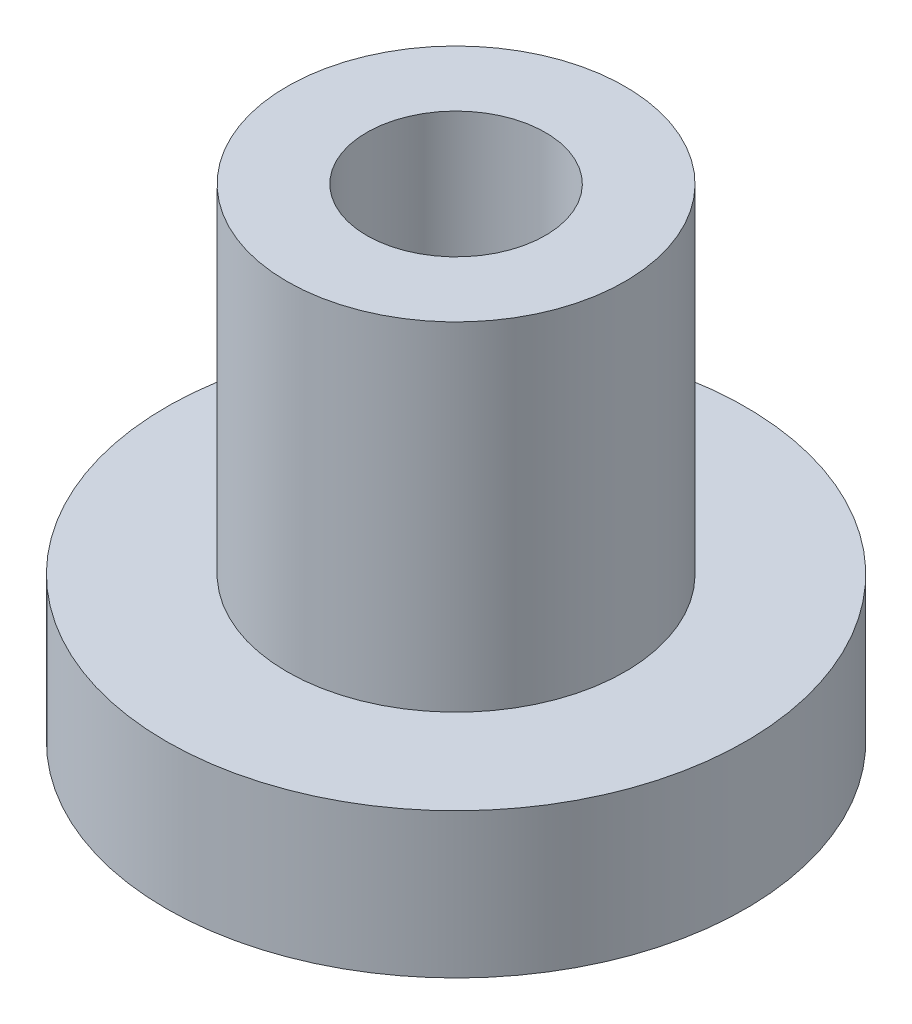
SolidWorks part; units mm, degrees
material "ABS"
ref_plane "前视基准面" through (0, 0, 0) normal (0, 0, 1) x (1, 0, 0)
ref_plane "上视基准面" through (0, 0, 0) normal (0, 1, 0) x (1, 0, 0)
ref_plane "右视基准面" through (0, 0, 0) normal (1, 0, 0) x (0, 0, -1)
sketch "草图1" plane through (0, 0, 0) normal (0, 1, 0) x (1, 0, 0)
  circle A0 centre (0, 0) radius 1.85
  circle A1 centre (0, 0) radius 6
  dimension "D1" = 12
  dimension "D2" = 3.7
extrude "凸台-拉伸1" add sketch "草图1" along normal blind 3
sketch "草图2" plane through (0, 3, 0) normal (0, 1, 0) x (1, 0, 0)
  circle A0 centre (0, 0) radius 1.85
  circle A1 centre (0, 0) radius 3.5
  dimension "D1" = 3.7
  dimension "D2" = 7
extrude "凸台-拉伸2" add sketch "草图2" along normal blind 7
